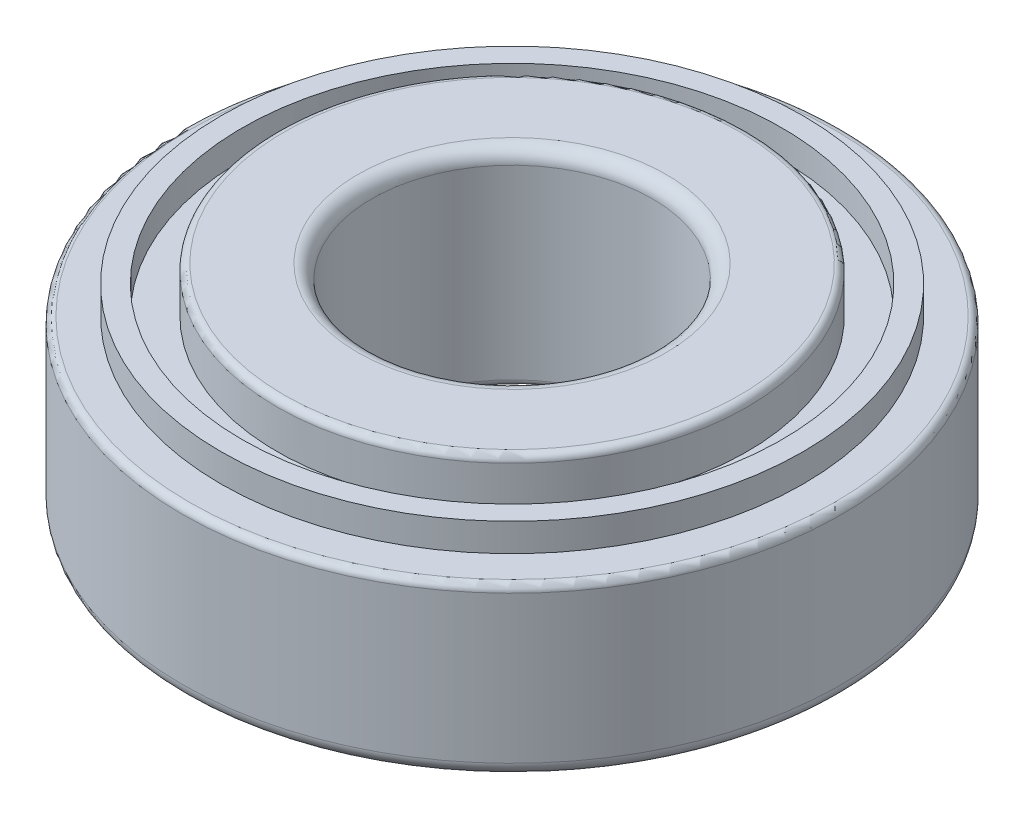
SolidWorks part; units mm, degrees
ref_plane "Front Plane" through (0, 0, 0) normal (0, 0, 1) x (1, 0, 0)
ref_plane "Top Plane" through (0, 0, 0) normal (0, 1, 0) x (1, 0, 0)
ref_plane "Right Plane" through (0, 0, 0) normal (1, 0, 0) x (0, 0, -1)
sketch "Sketch1" plane through (0, 0, 0) normal (0, 1, 0) x (1, 0, 0)
  circle A0 centre (0, 0) radius 23.5
  dimension "D1" = 47
extrude "Boss-Extrude1" add sketch "Sketch1" along normal blind 12
sketch "Sketch2" plane through (0, 12, 0) normal (0, 1, 0) x (1, 0, 0)
  circle A0 centre (0, 0) radius 16.75
  dimension "D1" = 33.5
extrude "Boss-Extrude2" add sketch "Sketch2" along normal blind 3.25
sketch "Sketch3" plane through (0, 15.25, 0) normal (0, 1, 0) x (1, 0, 0)
  circle A0 centre (0, 0) radius 10
  dimension "D1" = 20
extrude "Cut-Extrude1" cut sketch "Sketch3" against normal through all
sketch "Sketch5" plane through (0, 12, 0) normal (0, 1, 0) x (1, 0, 0)
  circle A0 centre (0, 0) radius 19.25
  circle A1 centre (0, 0) radius 20.75
  dimension "D1" = 38.5
  dimension "D2" = 41.5
extrude "Boss-Extrude3" add sketch "Sketch5" along normal blind 2
fillet "Fillet1" radius 1 1 edges at (0, 0, 23.5)
fillet "Fillet2" radius 1 1 edges at (0, 15.25, 10)
fillet "Fillet3" radius 0.5 1 edges at (0, 15.25, 16.75)
fillet "Fillet4" radius 0.5 2 edges at (0, 12, 23.5) (0, 0, 10)
sketch "Sketch6" plane through (0, 0, 0) normal (0, -1, 0) x (-1, 0, 0)
  circle A0 centre (0, 0) radius 18.5
  dimension "D1" = 37
extrude "Cut-Extrude2" cut sketch "Sketch6" against normal blind 0.5
fillet "Fillet5" radius 0.5 1 edges at (0, 0.5, 10)
